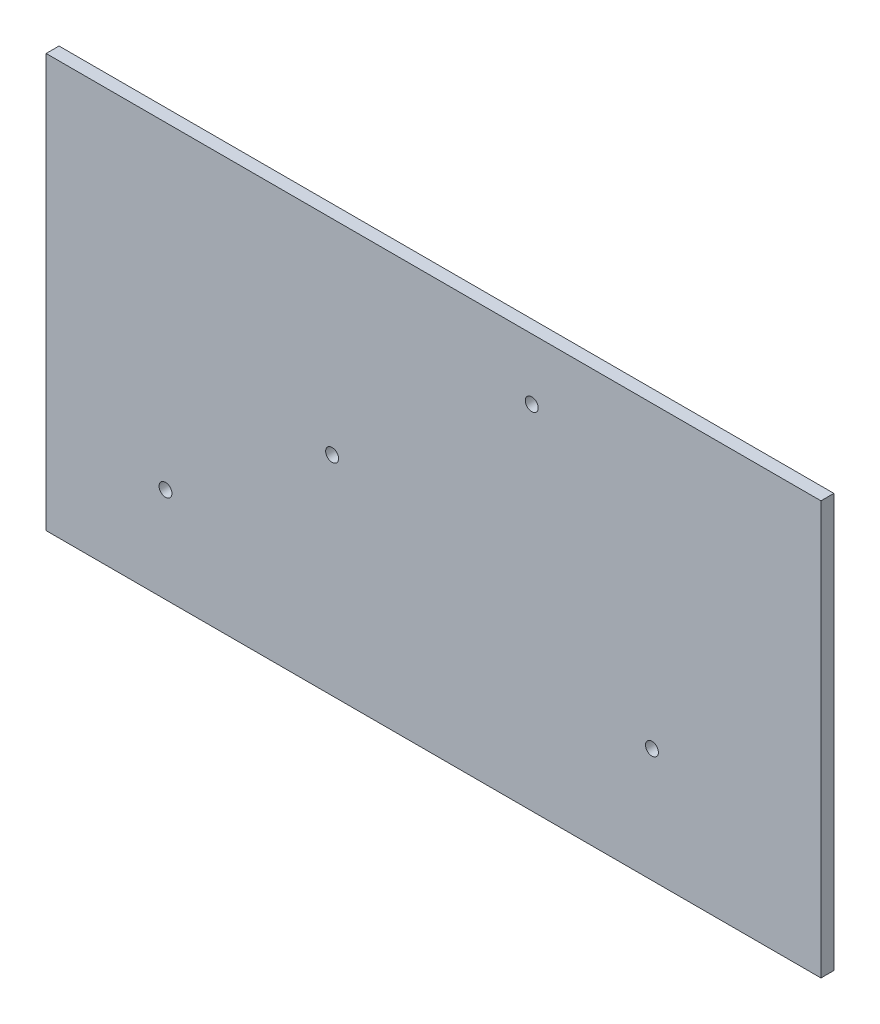
SolidWorks part; units mm, degrees
ref_plane "Front Plane" through (0, 0, 0) normal (0, 0, 1) x (1, 0, 0)
ref_plane "Top Plane" through (0, 0, 0) normal (0, 1, 0) x (1, 0, 0)
ref_plane "Right Plane" through (0, 0, 0) normal (1, 0, 0) x (0, 0, -1)
sketch "Sketch1" plane through (0, 0, 0) normal (0, 0, 1) x (1, 0, 0)
  line L1 (0, 0) -> (600, 0)
  line L2 (0, 0) -> (0, 320)
  line L3 (0, 320) -> (600, 320)
  line L4 (600, 0) -> (600, 320)
  circle A0 centre (221.4598, 161.5052) radius 5
  circle A1 centre (92.4365, 73.6134) radius 5
  circle A2 centre (376.0281, 272.777) radius 5
  circle A3 centre (469.1154, 88.3342) radius 5
  point P13 (92.4365, 73.6134)
  point P14 (221.4598, 161.5052)
  point P15 (376.0281, 272.777)
  dimension "D3" = 10
  dimension "D4" = 10
  dimension "D5" = 10
  dimension "D6" = 10
  dimension "D1" = 320
  dimension "D2" = 600
extrude "Boss-Extrude1" add sketch "Sketch1" along normal blind 10
